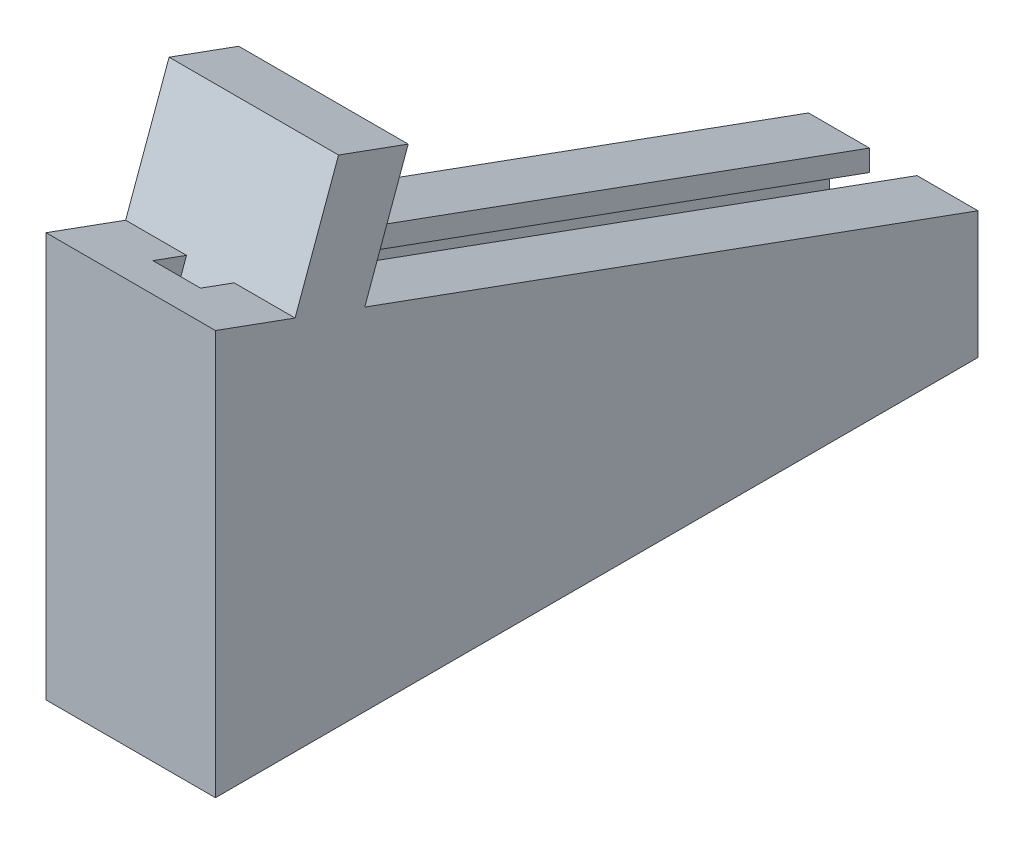
SolidWorks part; units mm, degrees
ref_plane "Front Plane" through (0, 0, 0) normal (0, 0, 1) x (1, 0, 0)
ref_plane "Top Plane" through (0, 0, 0) normal (0, 1, 0) x (1, 0, 0)
ref_plane "Right Plane" through (0, 0, 0) normal (1, 0, 0) x (0, 0, -1)
sketch "Sketch2" plane through (0, 0, 0) normal (1, 0, 0) x (0, 0, -1)
  line L0 (-10.9285, -9.7829) -> (25.0715, -9.7829)
  line L1 (25.0715, -9.7829) -> (25.0715, -3.7829)
  line L2 (25.0715, -3.7829) -> (-10.9285, 9.32)
  line L3 (-10.9285, 9.32) -> (-10.9285, -9.7829)
  dimension "D1" = 36
  dimension "D2" = 6
  dimension "D3" = 20
extrude "Boss-Extrude1" add sketch "Sketch2" against normal blind 8
sketch "Sketch3" plane through (0, 0, -25.0715) normal (0, 0, -1) x (-1, 0, 0)
  line L0 (2.875, -3.7829) -> (2.875, -4.7829)
  line L1 (8, -3.7829) -> (0, -3.7829) construction
  line L2 (2.875, -4.7829) -> (1, -4.7829)
  line L3 (1, -4.7829) -> (1, -6.7829)
  line L4 (1, -6.7829) -> (7, -6.7829)
  line L5 (7, -6.7829) -> (7, -4.7829)
  line L6 (7, -4.7829) -> (5.125, -4.7829)
  line L7 (5.125, -4.7829) -> (5.125, -3.7829)
  line L8 (5.125, -3.7829) -> (2.875, -3.7829)
  line L9 (0, -9.7829) -> (0, -3.7829) construction
  dimension "D1" = 6
  dimension "D2" = 1
  dimension "D3" = 2.25
  dimension "D4" = 2
  dimension "D5" = 1
sketch "Sketch5" plane through (-8, 0, 0) normal (-1, 0, 0) x (0, 0, 1)
  line L0 (-25.0715, -6.9755) -> (8.7574, 5.3372)
  line L1 (-25.0715, -9.7829) -> (-25.0715, -3.7829) construction
  line L3 (-25.0715, -3.7829) -> (10.9285, 9.32) construction
  dimension "D1" = 3
  dimension "D2" = 36
sweep "Cut-Sweep3" cut profiles "Sketch3" path "Sketch5"
sketch "Sketch6" plane through (-8, 0, 0) normal (-1, 0, 0) x (0, 0, 1)
  line L0 (4.9069, 3.9358) -> (8.1958, 5.1328)
  line L1 (4.9069, 3.9358) -> (1.8287, 12.393)
  line L2 (8.1958, 5.1328) -> (5.1176, 13.5901)
  line L3 (1.8287, 12.393) -> (5.1176, 13.5901)
  line L4 (-25.0715, -3.7829) -> (10.9285, 9.32) construction
  dimension "D1" = 9
  dimension "D2" = 3.5
  dimension "D3" = 3
  dimension "D4" = 4
extrude "Boss-Extrude2" add sketch "Sketch6" against normal blind 8
